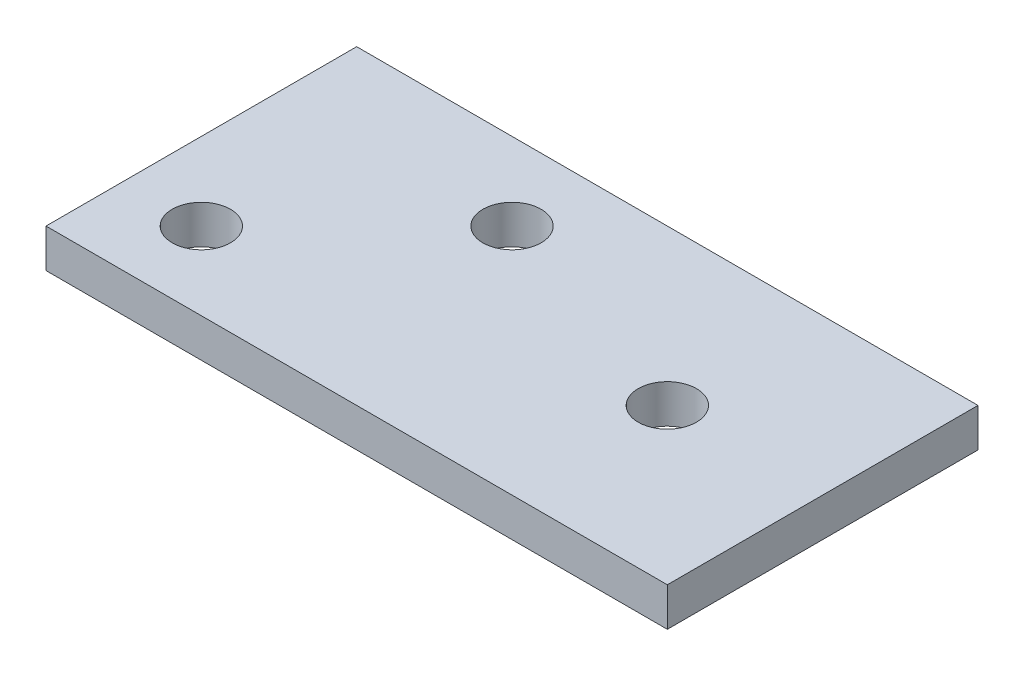
SolidWorks part; units mm, degrees
ref_plane "Alzado" through (0, 0, 0) normal (0, 0, 1) x (1, 0, 0)
ref_plane "Planta" through (0, 0, 0) normal (0, 1, 0) x (1, 0, 0)
ref_plane "Vista lateral" through (0, 0, 0) normal (1, 0, 0) x (0, 0, -1)
sketch "Croquis1" plane through (0, 0, 0) normal (0, 1, 0) x (1, 0, 0)
  line L1 (-50.8, 25.4) -> (50.8, 25.4)
  line L2 (-50.8, 25.4) -> (-50.8, -25.4)
  line L3 (-50.8, -25.4) -> (50.8, -25.4)
  line L4 (50.8, 25.4) -> (50.8, -25.4)
  line L5 (-50.8, 25.4) -> (50.8, -25.4) construction
  line L6 (-50.8, -25.4) -> (50.8, 25.4) construction
  point P0 (0, 0)
  dimension "D1" = 101.6
  dimension "D2" = 50.8
extrude "Saliente-Extruir1" add sketch "Croquis1" along normal blind 6.31
sketch "Croquis2" plane through (0, 6.31, 0) normal (0, 1, 0) x (1, 0, 0)
  line L0 (-50.8, 0) -> (50.8, 0) construction
  line L1 (-50.8, 25.4) -> (-50.8, -25.4) construction
  line L2 (50.8, -25.4) -> (50.8, 25.4) construction
  line L3 (50.8, 0) -> (0, 0) construction
  line L4 (0, 0) -> (25.4, 0) construction
  line L5 (25.4, 0) -> (25.4, 7.5763) construction
  line L6 (0, 0) -> (-50.8, 0) construction
  line L7 (-50.8, 0) -> (-25.4, 0) construction
  line L8 (-25.4, 0) -> (-25.4, 7.5763) construction
  line L9 (-25.4, 7.5763) -> (-18.1136, 12.9756) construction
  line L10 (-25.4, 0) -> (-50.8, -25.4) construction
  line L11 (-50.8, -25.4) -> (-25.4, 0) construction
  line L12 (0, 0) -> (0, 25.4) construction
  line L13 (50.8, 25.4) -> (-50.8, 25.4) construction
  line L14 (-25.4, 0) -> (-38.1, -12.7) construction
  line L15 (-38.1, -12.7) -> (-27.7316, -12.7) construction
  line L16 (-25.4, 0) -> (0, 25.4) construction
  line L17 (0, 25.4) -> (-12.7, 12.7) construction
  line L18 (-12.7, 12.7) -> (-7.8781, 12.7) construction
  circle A0 centre (-38.1, -12.7) radius 4.7625
  circle A1 centre (-12.7, 12.7) radius 4.7625
  dimension "D2" = 9.525
  dimension "D3" = 9.525
  dimension "D1" = 45
extrude "Cortar-Extruir1" cut sketch "Croquis2" against normal blind 6.31
sketch "Croquis3" plane through (0, 6.31, 0) normal (0, 1, 0) x (1, 0, 0)
  line L0 (50.8, 0) -> (0, 0) construction
  line L1 (50.8, -25.4) -> (50.8, 25.4) construction
  line L2 (0, 0) -> (25.4, 0) construction
  circle A0 centre (25.4, 0) radius 4.7625
  dimension "D1" = 9.525
extrude "Cortar-Extruir2" cut sketch "Croquis3" against normal blind 10
